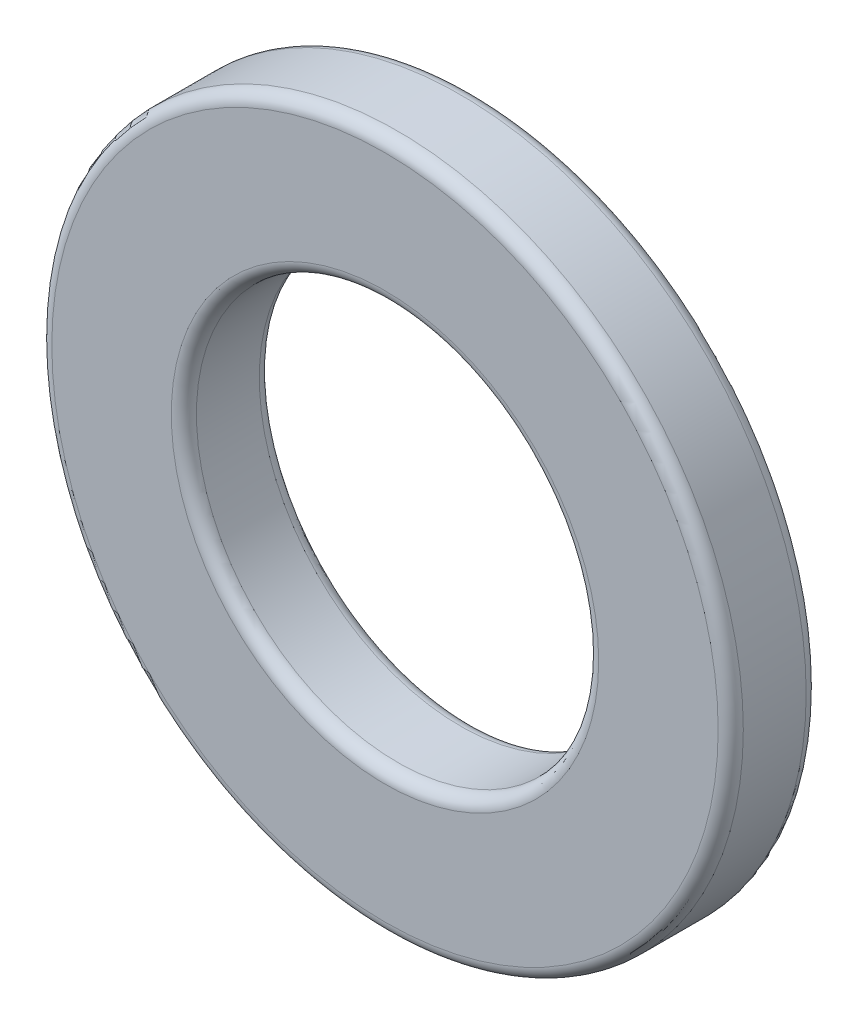
SolidWorks part; units mm, degrees
material "ABS PC"
ref_plane "Front Plane" through (0, 0, 0) normal (0, 0, 1) x (1, 0, 0)
ref_plane "Top Plane" through (0, 0, 0) normal (0, 1, 0) x (1, 0, 0)
ref_plane "Right Plane" through (0, 0, 0) normal (1, 0, 0) x (0, 0, -1)
sketch "Sketch1" plane through (0, 0, 0) normal (0, 0, 1) x (1, 0, 0)
  circle A0 centre (0, 0) radius 0.8
  circle A1 centre (0, 0) radius 1.375
  dimension "D1" = 1.6
  dimension "D2" = 2.75
extrude "Boss-Extrude1" add sketch "Sketch1" along normal blind 0.35
fillet "Fillet1" radius 0.05 4 edges at (0.8, 0, 0.35) (1.375, 0, 0.35) (0.8, 0, 0) (1.375, 0, 0)
